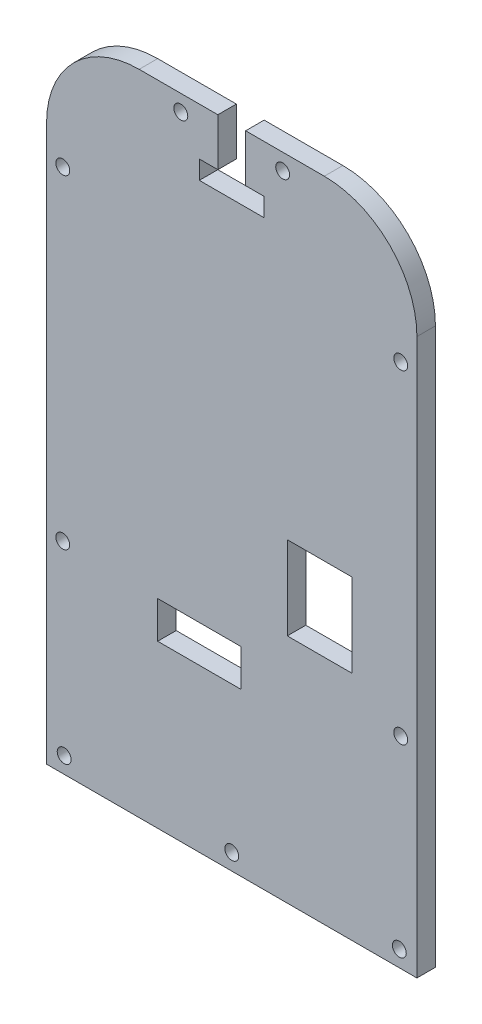
SolidWorks part; units mm, degrees
ref_plane "Alzado" through (0, 0, 0) normal (0, 0, 1) x (1, 0, 0)
ref_plane "Planta" through (0, 0, 0) normal (0, 1, 0) x (1, 0, 0)
ref_plane "Vista lateral" through (0, 0, 0) normal (1, 0, 0) x (0, 0, -1)
sketch "Croquis1" plane through (0, 0, 0) normal (0, 0, 1) x (1, 0, 0)
  line L1 (-19.9162, 25.8355) -> (20.0838, 25.8355)
  line L2 (-19.9162, 25.8355) -> (-19.9162, -44.1645)
  line L3 (-19.9162, -44.1645) -> (20.0838, -44.1645)
  line L4 (20.0838, 25.8355) -> (20.0838, -44.1645)
  dimension "D1" = 40
  dimension "D2" = 70
extrude "Saliente-Extruir1" add sketch "Croquis1" along normal blind 2
fillet "Redondeo1" radius 10 2 edges at (-19.9162, 25.8355, 1) (20.0838, 25.8355, 1)
sketch "Croquis2" plane through (0, 0, 0) normal (0, 0, -1) x (-1, 0, 0)
  line L54 (-10.0838, 25.8355) -> (9.9162, 25.8355) construction
  line L55 (-20.0838, -44.1645) -> (-20.0838, 15.8355) construction
  line L56 (19.9162, 15.8355) -> (19.9162, -44.1645) construction
  line L57 (19.9162, -44.1645) -> (-20.0838, -44.1645) construction
  circle A9 centre (-5.5838, 24.0855) radius 0.75
  circle A10 centre (5.4162, 24.0855) radius 0.75
  circle A11 centre (-18.1838, -42.4145) radius 0.75
  circle A12 centre (-0.0838, -42.4145) radius 0.75
  circle A13 centre (18.0162, -42.4145) radius 0.75
  circle A14 centre (-18.3338, 12.5855) radius 0.75
  circle A15 centre (-18.3338, -22.4145) radius 0.75
  circle A16 centre (18.1662, 12.5855) radius 0.75
  circle A17 centre (18.1662, -22.4145) radius 0.75
  point P34 (-0.0838, -44.1645)
  dimension "D1" = 1.5
  dimension "D2" = 1.75
  dimension "D3" = 14.5
  dimension "D4" = 14.5
  dimension "D5" = 1.75
  dimension "D6" = 1.75
  dimension "D7" = 1.75
  dimension "D8" = 1.9
  dimension "D9" = 1.9
  dimension "D10" = 20
  dimension "D11" = 35
extrude "Cortar-Extruir1" cut sketch "Croquis2" against normal up to next
sketch "Croquis3" plane through (0, 0, 0) normal (0, 0, -1) x (-1, 0, 0)
  line L0 (-10.0838, 25.8355) -> (9.9162, 25.8355) construction
  line L1 (-3.5838, 20.6974) -> (3.4162, 20.6974)
  line L2 (-3.5838, 20.6974) -> (-3.5838, 18.6974)
  line L3 (-3.5838, 18.6974) -> (3.4162, 18.6974)
  line L4 (3.4162, 20.6974) -> (3.4162, 18.6974)
  point P6 (-0.0838, 25.8355)
  point P7 (-0.0838, 20.6974)
  dimension "D1" = 2
  dimension "D2" = 7
extrude "Cortar-Extruir2" cut sketch "Croquis3" against normal up to next
sketch "Croquis4" plane through (0, 0, 0) normal (0, 0, -1) x (-1, 0, 0)
  line L0 (3.4162, 20.6974) -> (-3.5838, 20.6974) construction
  line L1 (-1.5838, 20.6974) -> (1.4162, 20.6974)
  line L2 (-1.5838, 20.6974) -> (-1.5838, 25.8355)
  line L3 (-1.5838, 25.8355) -> (1.4162, 25.8355)
  line L4 (1.4162, 20.6974) -> (1.4162, 25.8355)
  line L5 (-10.0838, 25.8355) -> (9.9162, 25.8355) construction
  line L6 (-20.0838, -44.1645) -> (-20.0838, 15.8355) construction
  line L7 (-13.0838, -10.1645) -> (-6.0838, -10.1645)
  line L8 (-13.0838, -10.1645) -> (-13.0838, -19.1645)
  line L9 (-13.0838, -19.1645) -> (-6.0838, -19.1645)
  line L10 (-6.0838, -10.1645) -> (-6.0838, -19.1645)
  line L11 (-1.0838, -22.6645) -> (7.9162, -22.6645)
  line L12 (-1.0838, -22.6645) -> (-1.0838, -26.6645)
  line L13 (-1.0838, -26.6645) -> (7.9162, -26.6645)
  line L14 (7.9162, -22.6645) -> (7.9162, -26.6645)
  line L15 (19.9162, -44.1645) -> (-20.0838, -44.1645) construction
  line L16 (19.9162, -44.1645) -> (-20.0838, -44.1645) construction
  line L17 (19.9162, 15.8355) -> (19.9162, -44.1645) construction
  dimension "D1" = 2
  dimension "D2" = 2
  dimension "D3" = 7
  dimension "D4" = 25
  dimension "D5" = 7
  dimension "D6" = 9
  dimension "D7" = 17.5
  dimension "D8" = 4
  dimension "D9" = 9
  dimension "D10" = 12
extrude "Cortar-Extruir3" cut sketch "Croquis4" against normal up to next
